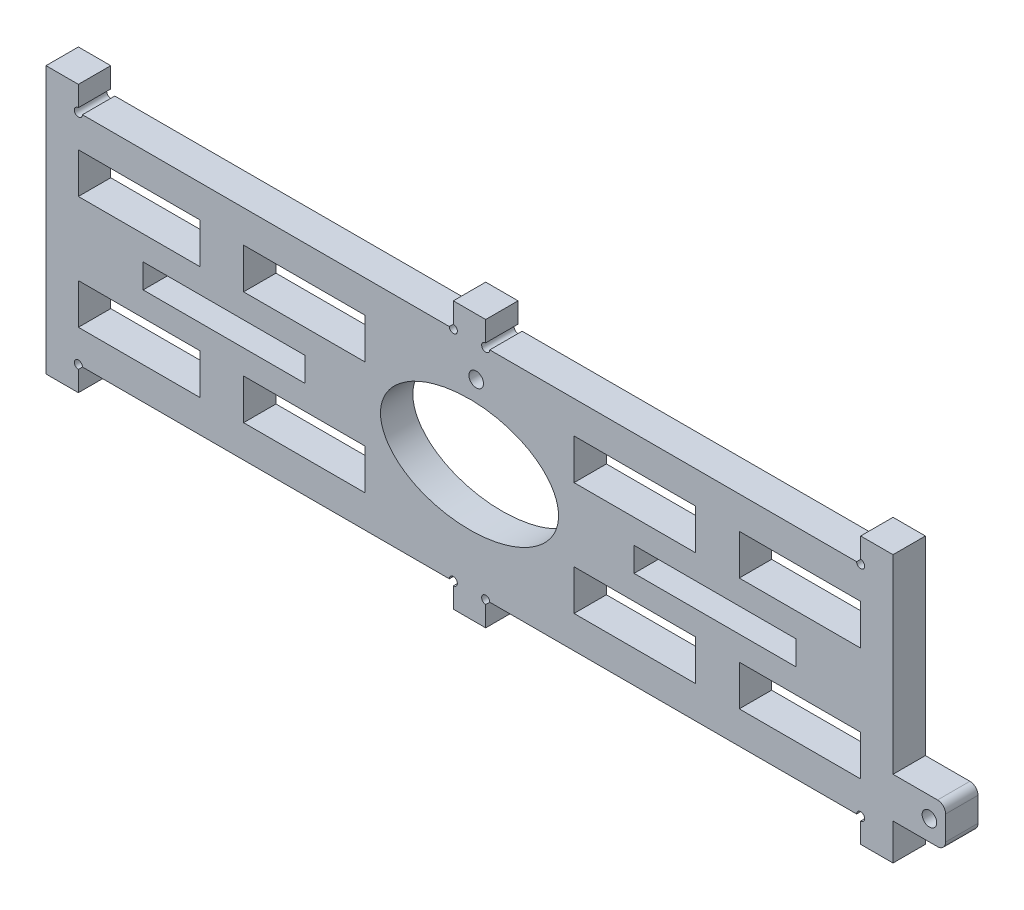
SolidWorks part; units mm, degrees
ref_plane "前视基准面" through (0, 0, 0) normal (0, 0, 1) x (1, 0, 0)
ref_plane "上视基准面" through (0, 0, 0) normal (0, 1, 0) x (1, 0, 0)
ref_plane "右视基准面" through (0, 0, 0) normal (1, 0, 0) x (0, 0, -1)
sketch "草图2" plane through (0, 0, 0) normal (0, 0, 1) x (1, 0, 0)
  line L0 (92.36, 3) -> (46.93, 3)
  line L1 (46.43, 0) -> (46.43, 2.5)
  line L2 (42.43, 0) -> (46.43, 0)
  line L3 (42.43, 0) -> (42.43, 2.5)
  line L4 (41.93, 3) -> (-3.5, 3)
  line L5 (-4, 0) -> (-4, 2.5)
  line L6 (-8, 0) -> (-4, 0)
  line L7 (-8, 35) -> (-8, 0)
  line L8 (92.86, 0) -> (92.86, 2.5)
  line L9 (96.86, 0) -> (92.86, 0)
  line L10 (96.86, 35) -> (96.86, 0)
  line L11 (92.36, 32) -> (46.93, 32)
  line L12 (46.43, 35) -> (46.43, 32.5)
  line L13 (42.43, 35) -> (46.43, 35)
  line L14 (42.43, 35) -> (42.43, 32.5)
  line L15 (41.93, 32) -> (-3.5, 32)
  line L16 (-4, 35) -> (-4, 32.5)
  line L17 (-8, 35) -> (-4, 35)
  line L18 (92.86, 35) -> (92.86, 32.5)
  line L19 (96.86, 35) -> (92.86, 35)
  arc A0 (46.93, 3) -> (46.43, 2.5) centre (46.43, 3) ccw
  arc A1 (42.43, 2.5) -> (41.93, 3) centre (42.43, 3) ccw
  arc A2 (-3.5, 3) -> (-4, 2.5) centre (-4, 3) ccw
  arc A3 (92.86, 2.5) -> (92.36, 3) centre (92.86, 3) ccw
  arc A4 (46.43, 32.5) -> (46.93, 32) centre (46.43, 32) ccw
  arc A5 (41.93, 32) -> (42.43, 32.5) centre (42.43, 32) ccw
  arc A6 (-4, 32.5) -> (-3.5, 32) centre (-4, 32) ccw
  arc A7 (92.36, 32) -> (92.86, 32.5) centre (92.86, 32) ccw
extrude "凸台-拉伸2" add sketch "草图2" along normal blind 4
ref_plane "基准面3" through (48.43, 0, 0) normal (1, 0, 0) x (0, 0, -1)
split "分割1" trim tools "基准面3" bodies to split 110 resulting bodies 111 112
move or copy body "实体-移动/复制1" bodies to move or copy 111 copy no translate (-0.1, 0, 0)
ref_plane "基准面4" through (40.43, 0, 0) normal (-1, 0, 0) x (0, 0, 1)
split "分割2" trim tools "基准面4" bodies to split 112 resulting bodies 114 115
move or copy body "实体-移动/复制2" bodies to move or copy 114 copy no translate (0.1, 0, 0)
combine bodies "组合2" operation type add bodies to combine 113 115 116
ref_plane "基准面5" through (0, 27, 0) normal (0, 1, 0) x (1, 0, 0)
split "分割3" trim tools "基准面5" bodies to split 118 resulting bodies 119 120
move or copy body "实体-移动/复制3" bodies to move or copy 119 copy no translate (0, -2, 0)
combine bodies "组合3" operation type add bodies to combine 121 120
sketch "草图3" plane through (0, 0, 0) normal (0, 0, -1) x (-1, 0, 0)
  line L0 (-96.76, 16.5) -> (32.0869, 16.5) construction
  line L1 (-96.76, 0) -> (-96.76, 33) construction
  line L3 (-102.26, 9.5) -> (-96.76, 9.5)
  line L4 (-103.26, 8.5) -> (-103.26, 5.5)
  line L5 (-102.26, 4.5) -> (-96.76, 4.5)
  line L6 (-96.76, 9.5) -> (-96.76, 4.5)
  circle A1 centre (-101.26, 7) radius 0.9
  arc A2 (-102.26, 4.5) -> (-103.26, 5.5) centre (-102.26, 5.5) cw
  arc A3 (-103.26, 8.5) -> (-102.26, 9.5) centre (-102.26, 8.5) cw
  point P16 (-103.26, 9.5)
  dimension "D3" = 14
  dimension "D4" = 1.8
  dimension "D5" = 2
  dimension "D6" = 2.5
  dimension "D7" = 1
  dimension "D1" = 6.5
  dimension "D2" = 5
extrude "凸台-拉伸3" add sketch "草图3" against normal blind 4
sketch "草图4" plane through (0, 0, 0) normal (0, 0, -1) x (-1, 0, 0)
  circle A0 centre (-45.26, 26) radius 0.9
  circle A1 centre (-101.26, 7) radius 0.9 construction
  dimension "D1" = 1.8
  dimension "D2" = 19
  dimension "D3" = 56
extrude "切除-拉伸1" cut sketch "草图4" against normal blind 10
sketch "草图5" plane through (0, 0, 0) normal (0, 0, -1) x (-1, 0, 0)
  line L0 (-69.595, 30) -> (-69.595, 3) construction
  line L1 (-92.76, 26) -> (-77.76, 26)
  line L2 (-92.76, 26) -> (-92.76, 21)
  line L3 (-92.76, 21) -> (-77.76, 21)
  line L4 (-77.76, 26) -> (-77.76, 21)
  line L5 (-92.26, 30) -> (-46.93, 30) construction
  line L6 (-46.93, 3) -> (-92.26, 3) construction
  line L7 (-69.595, 16.5) -> (-40.2022, 16.5) construction
  line L8 (-96.76, 9.5) -> (-96.76, 33) construction
  line L9 (-72.345, 26) -> (-57.345, 26)
  line L10 (-72.345, 26) -> (-72.345, 21)
  line L11 (-72.345, 21) -> (-57.345, 21)
  line L12 (-57.345, 26) -> (-57.345, 21)
  line L17 (-31.515, 26) -> (-16.515, 26)
  line L18 (-31.515, 26) -> (-31.515, 21)
  line L19 (-31.515, 21) -> (-16.515, 21)
  line L20 (-16.515, 26) -> (-16.515, 21)
  line L21 (-11.1, 26) -> (3.9, 26)
  line L22 (-11.1, 26) -> (-11.1, 21)
  line L23 (-11.1, 21) -> (3.9, 21)
  line L24 (3.9, 26) -> (3.9, 21)
  line L25 (7.9, 33) -> (7.9, 0) construction
  line L26 (-51.93, 26) -> (-36.93, 26) [skipped]
  line L27 (-51.93, 26) -> (-51.93, 21) [skipped]
  line L28 (-51.93, 21) -> (-36.93, 21) [skipped]
  line L29 (-36.93, 26) -> (-36.93, 21) [skipped]
  line L30 (3.9, 7) -> (3.9, 12)
  line L31 (-11.1, 12) -> (3.9, 12)
  line L32 (-11.1, 7) -> (-11.1, 12)
  line L33 (-11.1, 7) -> (3.9, 7)
  line L34 (-16.515, 7) -> (-16.515, 12)
  line L35 (-31.515, 12) -> (-16.515, 12)
  line L36 (-31.515, 7) -> (-31.515, 12)
  line L37 (-31.515, 7) -> (-16.515, 7)
  line L38 (-57.345, 7) -> (-57.345, 12)
  line L39 (-72.345, 12) -> (-57.345, 12)
  line L40 (-72.345, 7) -> (-72.345, 12)
  line L41 (-72.345, 7) -> (-57.345, 7)
  line L42 (-77.76, 7) -> (-77.76, 12)
  line L43 (-92.76, 12) -> (-77.76, 12)
  line L44 (-92.76, 7) -> (-92.76, 12)
  line L45 (-92.76, 7) -> (-77.76, 7)
  line L51 (-44.43, 0) -> (-44.43, 33) construction
  line L52 (-84.76, 18) -> (-64.76, 18)
  line L53 (-84.76, 18) -> (-84.76, 15)
  line L54 (-84.76, 15) -> (-64.76, 15)
  line L55 (-64.76, 18) -> (-64.76, 15)
  line L56 (-42.43, 0) -> (-46.43, 0) construction
  line L57 (-46.43, 33) -> (-42.43, 33) construction
  line L58 (-24.1, 18) -> (-24.1, 15)
  line L59 (-4.1, 15) -> (-24.1, 15)
  line L60 (-4.1, 18) -> (-4.1, 15)
  line L61 (-4.1, 18) -> (-24.1, 18)
  ellipse E0 centre (-44.43, 16.5) end of major axis (-33.43, 16.5) minor radius 7
  point P53 (0, 0)
  point P62 (-74.76, 18)
  point P74 (0, 0)
  dimension "D7" = 22
  dimension "D1" = 15
  dimension "D2" = 5
  dimension "D3" = 4
  dimension "D4" = 4
  dimension "D6" = 4
  dimension "D8" = 14
  dimension "D11" = 3
  dimension "D12" = 3
  dimension "D13" = 20
  dimension "D14" = 3
  dimension "D15" = 5.415
  dimension "D5" = 5
extrude "切除-拉伸2" cut sketch "草图5" against normal blind 10
